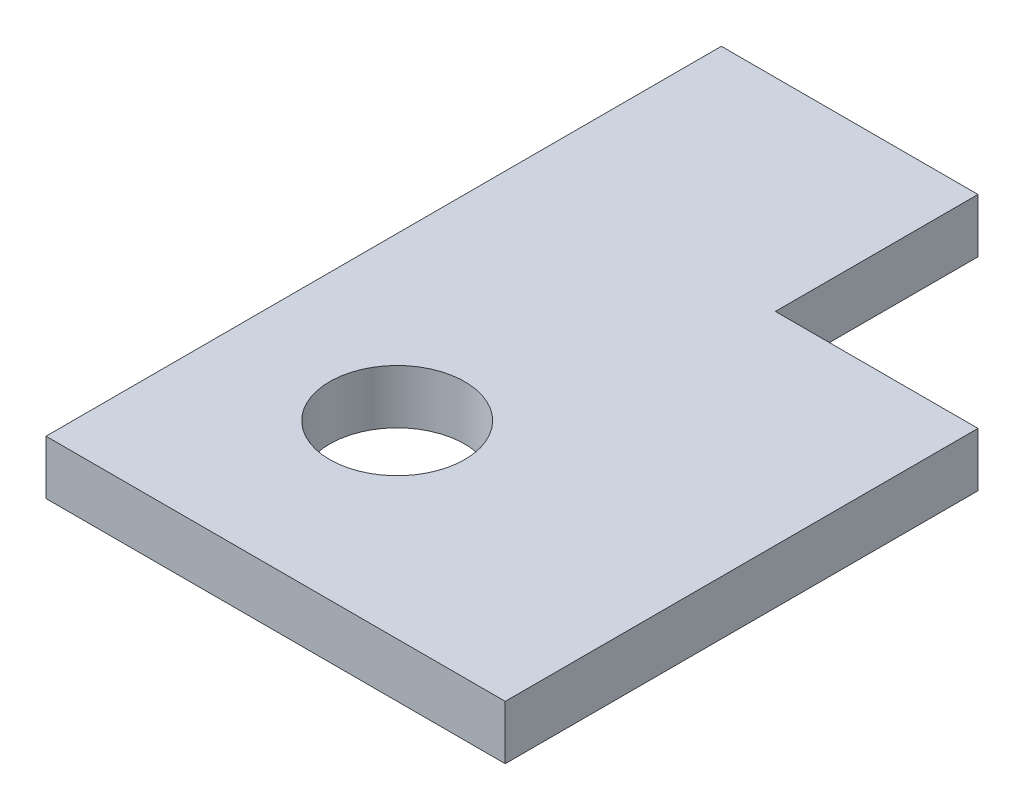
SolidWorks part; units mm, degrees
ref_plane "Płaszczyzna przednia" through (0, 0, 0) normal (0, 0, 1) x (1, 0, 0)
ref_plane "Płaszczyzna górna" through (0, 0, 0) normal (0, 1, 0) x (1, 0, 0)
ref_plane "Płaszczyzna prawa" through (0, 0, 0) normal (1, 0, 0) x (0, 0, -1)
sketch "Sketch1" plane through (0, 0, 0) normal (0, 1, 0) x (1, 0, 0)
  line L1 (0, 0) -> (34, 0)
  line L2 (0, 0) -> (0, 50)
  line L3 (0, 50) -> (19, 50)
  line L4 (34, 0) -> (34, 35)
  line L7 (34, 35) -> (19, 35)
  line L8 (19, 50) -> (19, 35)
  dimension "D1" = 15
  dimension "D2" = 15
  dimension "D3" = 34
  dimension "D4" = 50
extrude "Boss-Extrude1" add sketch "Sketch1" along normal blind 4
sketch "Sketch2" plane through (0, 4, 0) normal (0, 1, 0) x (1, 0, 0)
  line L0 (19, 35) -> (19, 50) construction
  line L1 (19, 50) -> (0, 50) construction
  circle A0 centre (12, 14) radius 5
  dimension "D1" = 10
  dimension "D2" = 7
  dimension "D3" = 36
extrude "Cut-Extrude1" cut sketch "Sketch2" against normal blind 4
